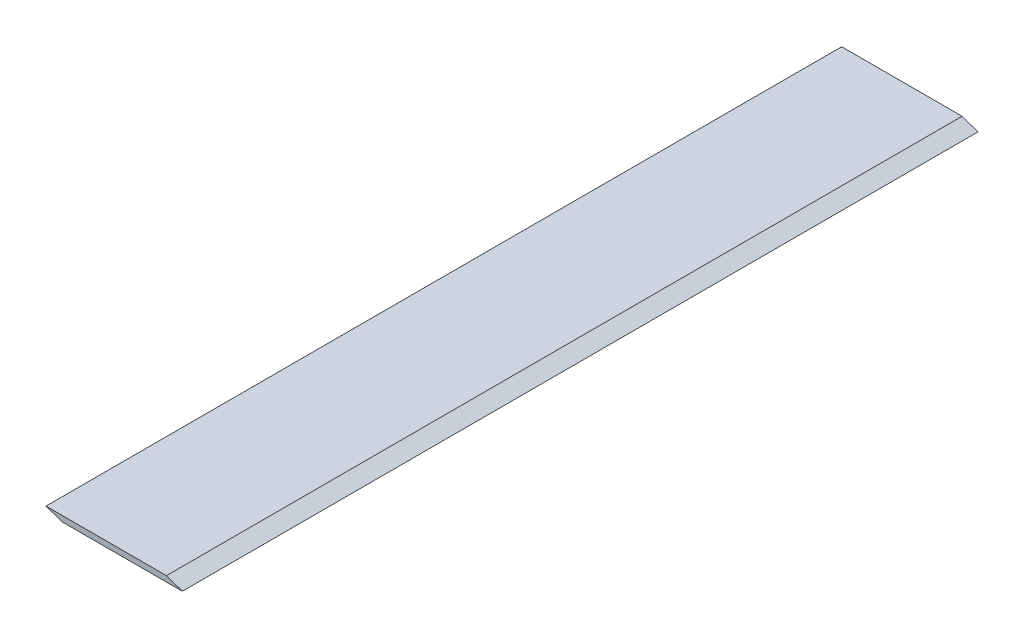
SolidWorks part; units mm, degrees
ref_plane "Alzado" through (0, 0, 0) normal (0, 0, 1) x (1, 0, 0)
ref_plane "Planta" through (0, 0, 0) normal (0, 1, 0) x (1, 0, 0)
ref_plane "Vista lateral" through (0, 0, 0) normal (1, 0, 0) x (0, 0, -1)
sketch "Croquis1" plane through (0, 0, 0) normal (0, 0, 1) x (1, 0, 0)
  line L0 (0, 0) -> (22, 0)
  line L1 (22, 0) -> (20, 0.7)
  line L2 (20, 0.7) -> (0, 0.7)
  line L3 (0, 0.7) -> (0, 0)
  dimension "D1" = 0.7
  dimension "D2" = 22
  dimension "D3" = 2
  dimension "D4" = 19.29
extrude "Saliente-Extruir1" add sketch "Croquis1" along normal blind 195
sketch "Croquis2" plane through (0, 0, 0) normal (0, -1, 0) x (1, 0, 0)
  line L1 (22.6607, 95) -> (0, 95)
  line L2 (22.6607, 95) -> (22.6607, 0)
  line L3 (22.6607, 0) -> (0, 0)
  line L4 (0, 95) -> (0, 0)
extrude "Cortar-Extruir1" cut sketch "Croquis2" against normal up to vertex (0.7 mm away)
sketch "Croquis3" plane through (0, 0, 95) normal (0, 0, -1) x (-1, 0, 0)
  line L0 (0, 0.7) -> (0, 0) construction
  line L1 (-20, 0.7) -> (0, 0.7) construction
  line L3 (-22, 0) -> (0, 0) construction
  line L4 (34.3955, 14.441) -> (-4.8646, 0.7) construction
  line L5 (0, 0) -> (0, 0.7)
  line L6 (0, 0.7) -> (-4.8646, 0.7)
  line L8 (-6.8646, 0) -> (0, 0)
  line L9 (-4.8646, 0.7) -> (-6.8646, 0)
extrude "Cortar-Extruir3" cut sketch "Croquis3" against normal up to vertex (100 mm away)
